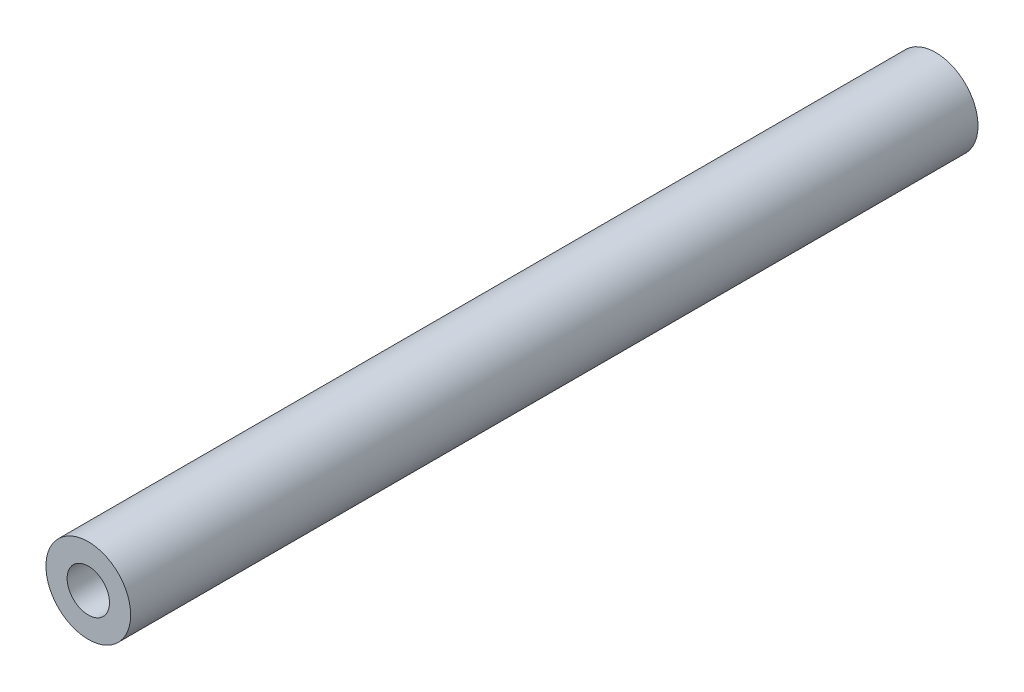
SolidWorks part; units mm, degrees
ref_plane "前视基准面" through (0, 0, 0) normal (0, 0, 1) x (1, 0, 0)
ref_plane "上视基准面" through (0, 0, 0) normal (0, 1, 0) x (1, 0, 0)
ref_plane "右视基准面" through (0, 0, 0) normal (1, 0, 0) x (0, 0, -1)
sketch "草图2" plane through (0, 0, 0) normal (0, 0, 1) x (1, 0, 0)
  circle A0 centre (0, 0) radius 5
  circle A1 centre (0, 0) radius 2.5
  dimension "D1" = 10
  dimension "D2" = 5
extrude "凸台-拉伸1" add sketch "草图2" along normal blind 100
